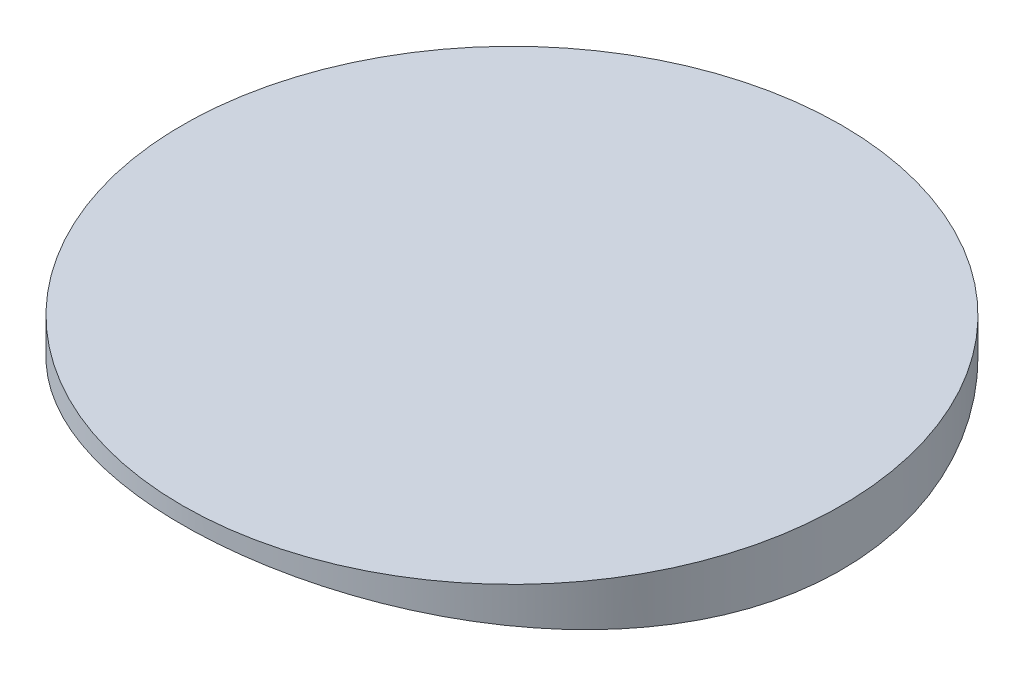
SolidWorks part; units mm, degrees
ref_plane "Front Plane" through (0, 0, 0) normal (0, 0, 1) x (1, 0, 0)
ref_plane "Top Plane" through (0, 0, 0) normal (0, 1, 0) x (1, 0, 0)
ref_plane "Right Plane" through (0, 0, 0) normal (1, 0, 0) x (0, 0, -1)
sketch "Sketch1" plane through (0, 0, 0) normal (0, 1, 0) x (1, 0, 0)
  circle A0 centre (0, 0) radius 17.75
  dimension "D1" = 35.5
extrude "Boss-Extrude1" add sketch "Sketch1" along normal blind 3
sketch "Sketch2" plane through (0, 0, 0) normal (0, 0, 1) x (1, 0, 0)
  line L5 (17.75, 0) -> (17.75, 3) construction
  line L6 (-17.75, 0) -> (17.75, 0)
  arc A2 (17.75, 0) -> (-17.75, 0) centre (0, -74.001) ccw
  point P7 (0, 2.099)
  dimension "D1" = 2.099
extrude "Cut-Extrude2" cut sketch "Sketch2" against normal through all both and the other way through all
